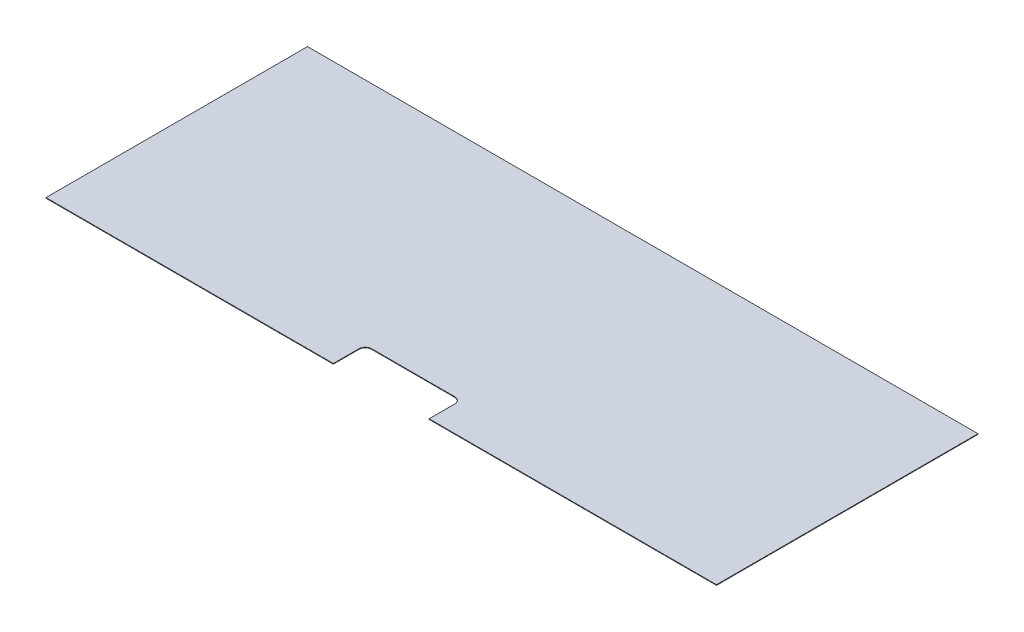
SolidWorks part; units mm, degrees
ref_plane "Front Plane" through (0, 0, 0) normal (0, 0, 1) x (1, 0, 0)
ref_plane "Top Plane" through (0, 0, 0) normal (0, 1, 0) x (1, 0, 0)
ref_plane "Right Plane" through (0, 0, 0) normal (1, 0, 0) x (0, 0, -1)
sketch "Sketch1" plane through (0, 0, 0) normal (0, 1, 0) x (1, 0, 0)
  line L1 (506.0901, 123.7057) -> (-543.9099, 123.7057)
  line L2 (506.0901, 123.7057) -> (506.0901, 533.2057)
  line L3 (506.0901, 533.2057) -> (-543.9099, 533.2057)
  line L4 (-543.9099, 123.7057) -> (-543.9099, 533.2057)
  dimension "D1" = 1050
  dimension "D2" = 409.5
extrude "Boss-Extrude1" add sketch "Sketch1" along normal blind 1
sketch "Sketch2" plane through (0, 1, 0) normal (0, 1, 0) x (1, 0, 0)
  line L0 (-543.9099, 123.7057) -> (506.0901, 123.7057) construction
  line L1 (-93.9099, 123.7057) -> (56.0901, 123.7057)
  line L2 (-93.9099, 123.7057) -> (-93.9099, 173.7057)
  line L3 (-93.9099, 173.7057) -> (56.0901, 173.7057)
  line L4 (56.0901, 123.7057) -> (56.0901, 173.7057)
  line L5 (506.0901, 123.7057) -> (506.0901, 533.2057) construction
  line L6 (-543.9099, 533.2057) -> (-543.9099, 123.7057) construction
  dimension "D1" = 50
  dimension "D2" = 150
  dimension "D3" = 450
  dimension "D4" = 450
extrude "Cut-Extrude1" cut sketch "Sketch2" against normal blind 1
fillet "Fillet1" radius 10 2 edges at (56.0901, 0.5, -173.7057) (-93.9099, 0.5, -173.7057)
